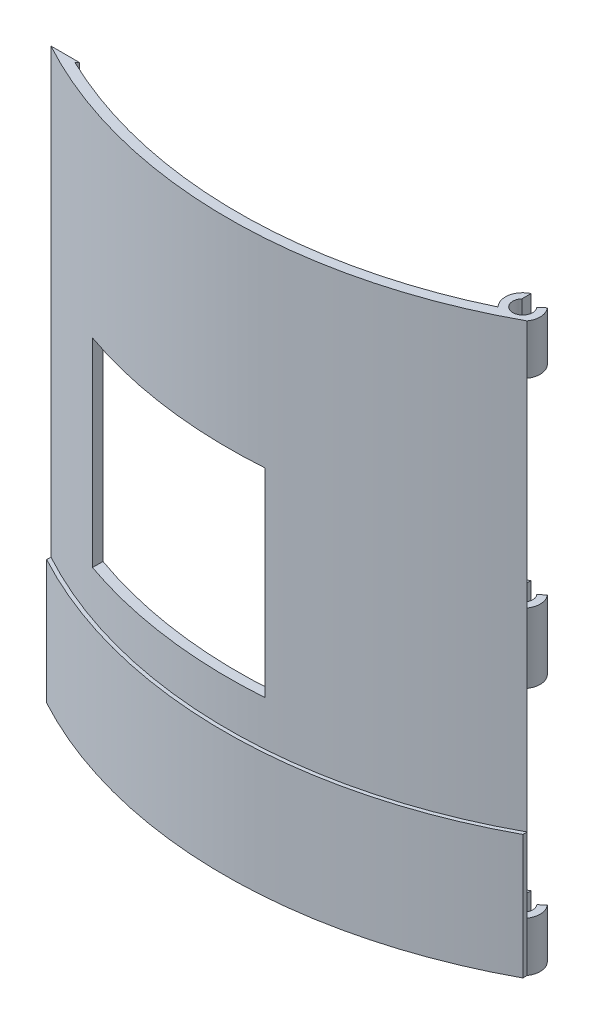
SolidWorks part; units mm, degrees
ref_plane "前视基准面" through (0, 0, 0) normal (0, 0, 1) x (1, 0, 0)
ref_plane "上视基准面" through (0, 0, 0) normal (0, 1, 0) x (1, 0, 0)
ref_plane "右视基准面" through (0, 0, 0) normal (1, 0, 0) x (0, 0, -1)
sketch "草图1" plane through (0, 0, 0) normal (0, 1, 0) x (1, 0, 0)
  line L0 (0, 0) -> (94, 0) construction
  line L1 (47, 0) -> (47, 58.1905) construction
  line L4 (92, 0) -> (92, 8.8253) construction
  line L5 (90.5, 3.3229) -> (90.5, 5.1623)
  line L7 (2, 0) -> (2, 8.8253) construction
  line L8 (0.5, 3.3229) -> (0.5, 5.1623)
  line L9 (3.5, 3.3229) -> (3.5, 5.1623)
  line L10 (93.5, 3.3229) -> (94.625, 4.315)
  arc A0 (-0.8723, 0) -> (94.8723, 0) centre (47, 87.7966) ccw
  arc A1 (4.4604, -0.4892) -> (89.5396, -0.4892) centre (47, 87.7966) ccw
  arc A2 (94.8723, 0) -> (94.625, 4.315) centre (92, 2) ccw
  arc A3 (90.5, 3.3229) -> (93.5, 3.3229) centre (92, 2) ccw
  arc A4 (90.5, 5.1623) -> (89.5396, -0.4892) centre (92, 2) ccw
  arc A5 (-0.8723, 0) -> (0.5, 5.1623) centre (2, 2) cw
  arc A6 (3.5, 5.1623) -> (4.4604, -0.4892) centre (2, 2) cw
  arc A7 (3.5, 3.3229) -> (0.5, 3.3229) centre (2, 2) cw
  dimension "D2" = 200
  dimension "D3" = 196
  dimension "D4" = 1.5
  dimension "D5" = 4
  dimension "D1" = 94
  dimension "D6" = 2
  dimension "D7" = 2
  dimension "D8" = 3
extrude "凸台-拉伸1" add sketch "草图1" along normal blind 114
sketch "草图3" plane through (0, 0, 0) normal (0, -1, 0) x (1, 0, 0)
  line L0 (47, 12.2034) -> (47, -39.7184) construction
  line L1 (-0.8723, 0) -> (-0.8723, 0.8533)
  line L2 (94.8723, 0) -> (94.8723, 0.8533)
  arc A0 (94.8723, 0) -> (-0.8723, 0) centre (47, -87.7966) ccw construction
  arc A1 (94.8723, 0) -> (-0.8723, 0) centre (47, -87.7966) ccw
  arc A2 (94.8723, 0.8533) -> (-0.8723, 0.8533) centre (47, -87.7966) ccw
  dimension "D2" = 201.5
extrude "凸台-拉伸2" add sketch "草图3" against normal blind 25
sketch "草图4" plane through (0, 0, 0) normal (0, 0, 1) x (1, 0, 0)
  line L0 (4.4604, 0) -> (89.5396, 0) construction
  line L1 (100.7687, 104) -> (84.5309, 104)
  line L2 (100.7687, 104) -> (100.7687, 64)
  line L3 (100.7687, 10) -> (84.5309, 10)
  line L4 (84.5309, 104) -> (84.5309, 64)
  line L5 (-8.4538, 64) -> (10.3883, 64)
  line L6 (-8.4538, 64) -> (-8.4538, 114)
  line L7 (-8.4538, 114) -> (10.3883, 114)
  line L8 (10.3883, 64) -> (10.3883, 114)
  line L9 (-8.4538, 0) -> (11.4606, 0)
  line L10 (-8.4538, 0) -> (-8.4538, 50)
  line L11 (-8.4538, 50) -> (11.4606, 50)
  line L12 (11.4606, 0) -> (11.4606, 50)
  line L13 (89.5396, 114) -> (4.4604, 114) construction
  line L14 (90, 0) -> (94, 0) construction
  line L15 (100.7687, 64) -> (84.5309, 64)
  line L16 (84.5309, 50) -> (100.7687, 50)
  line L17 (100.7687, 50) -> (100.7687, 10)
  line L18 (84.5309, 50) -> (84.5309, 10)
  dimension "D1" = 50
  dimension "D2" = 50
  dimension "D3" = 10
  dimension "D4" = 10
extrude "切除-拉伸1" cut sketch "草图4" against normal blind 20
sketch "草图5" plane through (0, 0, 0) normal (0, 0, 1) x (1, 0, 0)
  line L0 (94.8723, 114) -> (-0.8723, 114) construction
  line L1 (14.1277, 74) -> (54.1277, 74)
  line L2 (14.1277, 74) -> (14.1277, 34)
  line L3 (14.1277, 34) -> (54.1277, 34)
  line L4 (54.1277, 74) -> (54.1277, 34)
  line L5 (-0.8723, 25) -> (-0.8723, 50) construction
  dimension "D1" = 40
  dimension "D2" = 40
  dimension "D3" = 15
  dimension "D4" = 40
extrude "切除-拉伸2" cut sketch "草图5" along normal blind 20
